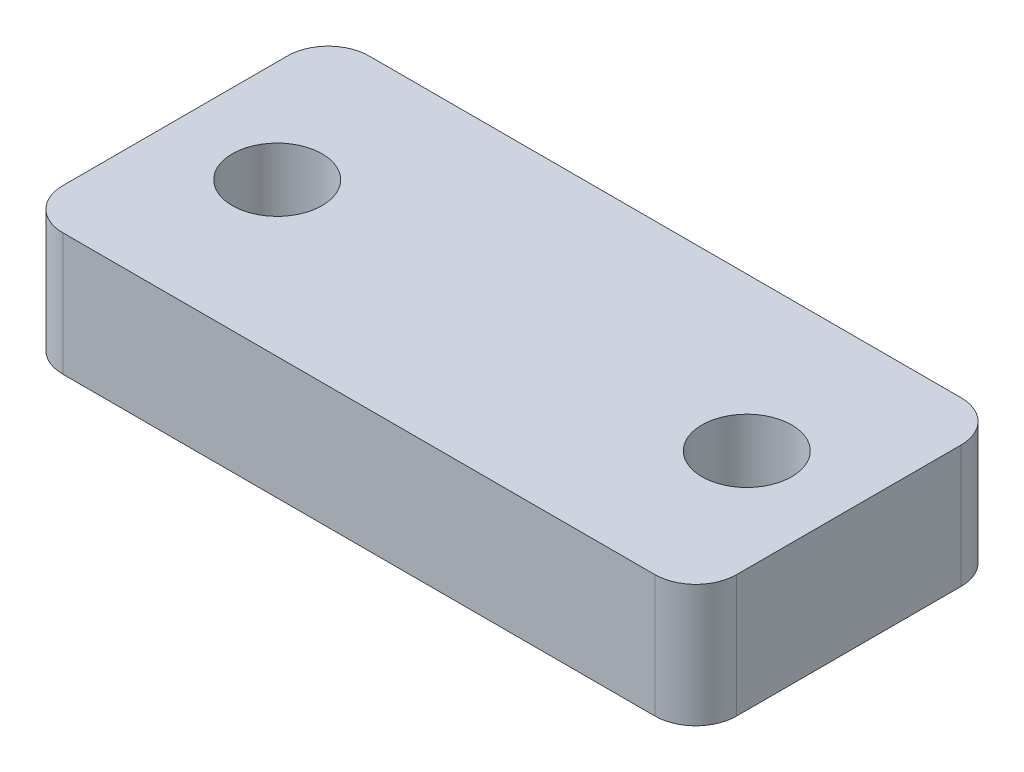
SolidWorks part; units mm, degrees
material "ABS"
ref_plane "前视基准面" through (0, 0, 0) normal (0, 0, 1) x (1, 0, 0)
ref_plane "上视基准面" through (0, 0, 0) normal (0, 1, 0) x (1, 0, 0)
ref_plane "右视基准面" through (0, 0, 0) normal (1, 0, 0) x (0, 0, -1)
sketch "草图1" plane through (0, 0, 0) normal (0, 1, 0) x (1, 0, 0)
  line L0 (-16.5, 0) -> (16.5, 0) construction
  line L1 (-16.5, 7.5) -> (16.5, 7.5)
  line L2 (-16.5, 7.5) -> (-16.5, -7.5)
  line L3 (-16.5, -7.5) -> (16.5, -7.5)
  line L4 (16.5, 7.5) -> (16.5, -7.5)
  line L5 (0, -3.3) -> (0, 3.3) construction
  circle A0 centre (-11.5, 0) radius 2.2
  circle A2 centre (11.5, 0) radius 2.2
  dimension "D3" = 23
  dimension "D4" = 4.4
  dimension "D1" = 33
  dimension "D2" = 15
extrude "凸台-拉伸1" add sketch "草图1" along normal blind 6
fillet "圆角1" radius 2 4 edges at (-16.5, 3, 7.5) (-16.5, 3, -7.5) (16.5, 3, -7.5) (16.5, 3, 7.5)
